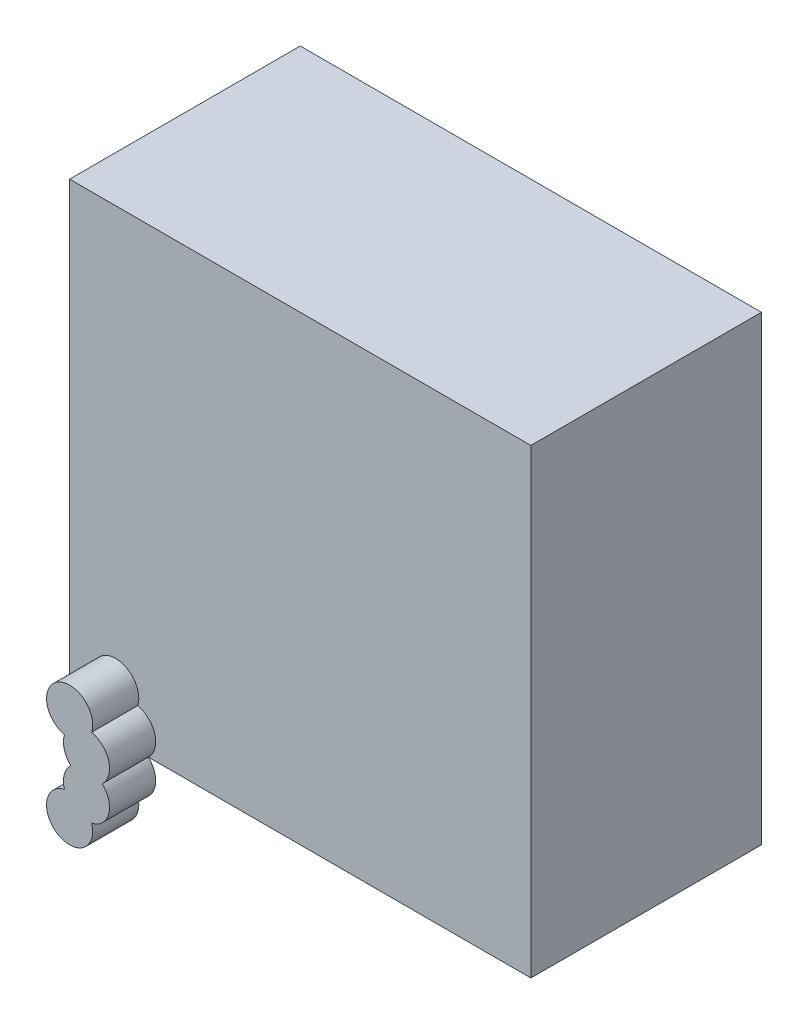
SolidWorks part; units mm, degrees
ref_plane "前视基准面" through (0, 0, 0) normal (0, 0, 1) x (1, 0, 0)
ref_plane "上视基准面" through (0, 0, 0) normal (0, 1, 0) x (1, 0, 0)
ref_plane "右视基准面" through (0, 0, 0) normal (1, 0, 0) x (0, 0, -1)
other "Configuration Table"
sketch "草图1" plane through (0, 0, 0) normal (0, 0, 1) x (1, 0, 0)
  line L1 (0, 0) -> (20, 0)
  line L2 (0, 0) -> (0, 20)
  line L3 (0, 20) -> (20, 20)
  line L4 (20, 0) -> (20, 20)
extrude "BaseBox" add sketch "草图1" along normal blind 10
sketch "草图2" plane through (0, 0, 10) normal (0, 0, 1) x (1, 0, 0)
  circle A0 centre (2, 2) radius 1
extrude "BossSeed" add sketch "草图2" along normal blind 2
pattern_circular "CircularPattern" count 4 every 30 about axis through (0, 0, 0) along (0, 0, 1) of "BossSeed"
